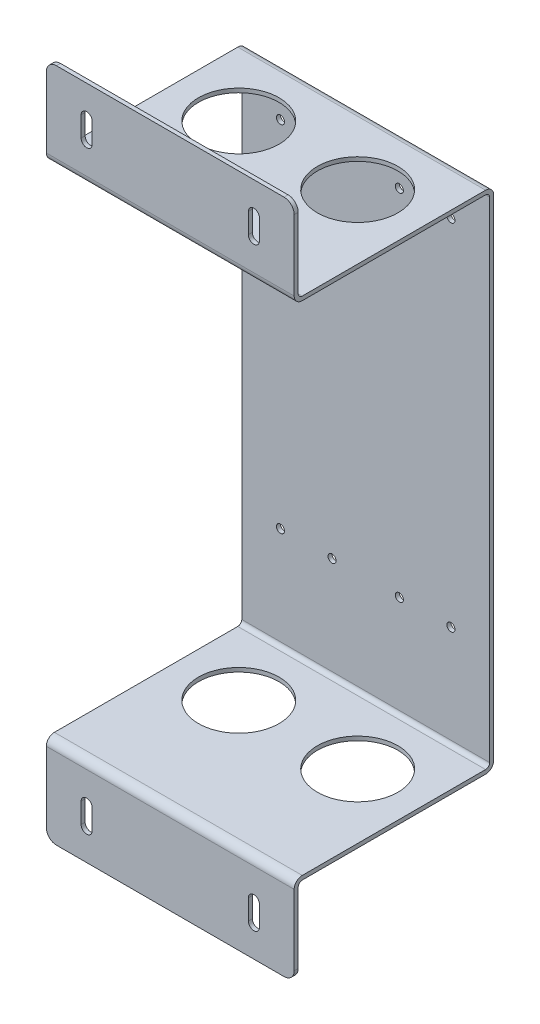
SolidWorks part; units mm, degrees
ref_plane "前视基准面" through (0, 0, 0) normal (0, 0, 1) x (1, 0, 0)
ref_plane "上视基准面" through (0, 0, 0) normal (0, 1, 0) x (1, 0, 0)
ref_plane "右视基准面" through (0, 0, 0) normal (1, 0, 0) x (0, 0, -1)
ref_plane "基准面1" through (0, 0, 49.5) normal (0, 0, 1) x (1, 0, 0)
sketch "草图1" plane through (0, 0, 49.5) normal (0, 0, 1) x (1, 0, 0)
  line L0 (-13.5, -167.5) -> (-13.5, 167.5)
  line L1 (-13.5, 167.5) -> (-136.5, 167.5)
  line L2 (-136.5, 167.5) -> (-136.5, -167.5)
  line L3 (-136.5, -167.5) -> (-13.5, -167.5)
extrude "凸台-拉伸1" add sketch "草图1" against normal blind 99
sketch "草图2" plane through (-13.5, 0, 0) normal (1, 0, 0) x (0, 0, -1)
  line L0 (-49.5, 123.5) -> (-49.5, -123.5)
  line L1 (-49.5, -123.5) -> (47.5, -123.5)
  line L2 (47.5, -123.5) -> (47.5, 123.5)
  line L3 (47.5, 123.5) -> (-49.5, 123.5)
extrude "切除-拉伸1" cut sketch "草图2" against normal through all
sketch "草图3" plane through (-13.5, 0, 0) normal (1, 0, 0) x (0, 0, -1)
  line L0 (49.5, 167.5) -> (-47.5, 167.5)
  line L1 (-47.5, 167.5) -> (-47.5, 125.5)
  line L2 (-47.5, 125.5) -> (49.5, 125.5)
  line L3 (49.5, 125.5) -> (49.5, 167.5)
extrude "切除-拉伸2" cut sketch "草图3" against normal through all
sketch "草图4" plane through (-13.5, 0, 0) normal (1, 0, 0) x (0, 0, -1)
  line L0 (49.5, -167.5) -> (49.5, -125.5)
  line L1 (49.5, -125.5) -> (-47.5, -125.5)
  line L2 (-47.5, -125.5) -> (-47.5, -167.5)
  line L3 (-47.5, -167.5) -> (49.5, -167.5)
extrude "切除-拉伸3" cut sketch "草图4" against normal through all
sketch "草图5" plane through (0, 0, 49.5) normal (0, 0, 1) x (1, 0, 0)
  line L0 (-30.75, 142.5) -> (-30.75, 152.5)
  line L1 (-36.25, 152.5) -> (-36.25, 142.5)
  arc A0 (-36.25, 142.5) -> (-30.75, 142.5) centre (-33.5, 142.5) ccw
  arc A1 (-30.75, 152.5) -> (-36.25, 152.5) centre (-33.5, 152.5) ccw
extrude "切除-拉伸4" cut sketch "草图5" against normal through all
sketch "草图6" plane through (0, 0, 47.5) normal (0, 0, -1) x (-1, 0, 0)
  line L0 (113.75, 152.5) -> (113.75, 142.5)
  line L1 (119.25, 142.5) -> (119.25, 152.5)
  arc A0 (119.25, 152.5) -> (113.75, 152.5) centre (116.5, 152.5) ccw
  arc A1 (113.75, 142.5) -> (119.25, 142.5) centre (116.5, 142.5) ccw
extrude "切除-拉伸5" cut sketch "草图6" against normal through all
sketch "草图7" plane through (0, 0, 49.5) normal (0, 0, 1) x (1, 0, 0)
  line L0 (-30.75, -152.5) -> (-30.75, -142.5)
  line L1 (-36.25, -142.5) -> (-36.25, -152.5)
  arc A0 (-36.25, -152.5) -> (-30.75, -152.5) centre (-33.5, -152.5) ccw
  arc A1 (-30.75, -142.5) -> (-36.25, -142.5) centre (-33.5, -142.5) ccw
extrude "切除-拉伸6" cut sketch "草图7" against normal through all
sketch "草图8" plane through (0, 0, 47.5) normal (0, 0, -1) x (-1, 0, 0)
  line L0 (113.75, -142.5) -> (113.75, -152.5)
  line L1 (119.25, -152.5) -> (119.25, -142.5)
  arc A0 (119.25, -142.5) -> (113.75, -142.5) centre (116.5, -142.5) ccw
  arc A1 (113.75, -152.5) -> (119.25, -152.5) centre (116.5, -152.5) ccw
extrude "切除-拉伸7" cut sketch "草图8" against normal through all
hole_wizard "M4 螺纹孔1" positions "草图10" profile "草图9" tap size "M4" standard "ISO" end condition through all
sketch "草图10" plane through (0, 0, -47.5) normal (0, 0, 1) x (1, 0, 0)
  point P0 (-117.3, -72.9)
sketch "草图9" plane through (-117.3, -72.9, -47.5) normal (1, 0, 0) x (0, -1, 0)
  line L0 (0, 0) -> (0, 2)
  line L1 (0, 2) -> (2, 2)
  line L2 (2, 2) -> (2, 0)
  line L5 (2, 0) -> (0, 0)
  line L11 (0, -6.35) -> (0, 107.95) construction
  dimension "螺纹线主直径" = 4
  dimension "通孔螺纹孔钻头深度" = 2
hole_wizard "M4 螺纹孔2" positions "草图12" profile "草图11" tap size "M4" standard "ISO" end condition through all
sketch "草图12" plane through (0, 0, -47.5) normal (0, 0, 1) x (1, 0, 0)
  point P0 (-91.7, -72.9)
sketch "草图11" plane through (-91.7, -72.9, -47.5) normal (1, 0, 0) x (0, -1, 0)
  line L0 (0, 0) -> (0, 2)
  line L1 (0, 2) -> (2, 2)
  line L2 (2, 2) -> (2, 0)
  line L5 (2, 0) -> (0, 0)
  line L11 (0, -6.35) -> (0, 107.95) construction
  dimension "螺纹线主直径" = 4
  dimension "通孔螺纹孔钻头深度" = 2
hole_wizard "M4 螺纹孔3" positions "草图14" profile "草图13" tap size "M4" standard "ISO" end condition through all
sketch "草图14" plane through (0, 0, -47.5) normal (0, 0, 1) x (1, 0, 0)
  point P0 (-32.7, -72.9)
sketch "草图13" plane through (-32.7, -72.9, -47.5) normal (1, 0, 0) x (0, -1, 0)
  line L0 (0, 0) -> (0, 2)
  line L1 (0, 2) -> (2, 2)
  line L2 (2, 2) -> (2, 0)
  line L5 (2, 0) -> (0, 0)
  line L11 (0, -6.35) -> (0, 107.95) construction
  dimension "螺纹线主直径" = 4
  dimension "通孔螺纹孔钻头深度" = 2
hole_wizard "M4 螺纹孔4" positions "草图16" profile "草图15" tap size "M4" standard "ISO" end condition through all
sketch "草图16" plane through (0, 0, -47.5) normal (0, 0, 1) x (1, 0, 0)
  point P0 (-58.3, -72.9)
sketch "草图15" plane through (-58.3, -72.9, -47.5) normal (1, 0, 0) x (0, -1, 0)
  line L0 (0, 0) -> (0, 2)
  line L1 (0, 2) -> (2, 2)
  line L2 (2, 2) -> (2, 0)
  line L5 (2, 0) -> (0, 0)
  line L11 (0, -6.35) -> (0, 107.95) construction
  dimension "螺纹线主直径" = 4
  dimension "通孔螺纹孔钻头深度" = 2
hole_wizard "M4 螺纹孔5" positions "草图18" profile "草图17" tap size "M4" standard "ISO" end condition through all
sketch "草图18" plane through (0, 0, -47.5) normal (0, 0, 1) x (1, 0, 0)
  point P0 (-91.7, 102.9)
sketch "草图17" plane through (-91.7, 102.9, -47.5) normal (1, 0, 0) x (0, -1, 0)
  line L0 (0, 0) -> (0, 2)
  line L1 (0, 2) -> (2, 2)
  line L2 (2, 2) -> (2, 0)
  line L5 (2, 0) -> (0, 0)
  line L11 (0, -6.35) -> (0, 107.95) construction
  dimension "螺纹线主直径" = 4
  dimension "通孔螺纹孔钻头深度" = 2
hole_wizard "M4 螺纹孔6" positions "草图20" profile "草图19" tap size "M4" standard "ISO" end condition through all
sketch "草图20" plane through (0, 0, -47.5) normal (0, 0, 1) x (1, 0, 0)
  point P0 (-117.3, 102.9)
sketch "草图19" plane through (-117.3, 102.9, -47.5) normal (1, 0, 0) x (0, -1, 0)
  line L0 (0, 0) -> (0, 2)
  line L1 (0, 2) -> (2, 2)
  line L2 (2, 2) -> (2, 0)
  line L5 (2, 0) -> (0, 0)
  line L11 (0, -6.35) -> (0, 107.95) construction
  dimension "螺纹线主直径" = 4
  dimension "通孔螺纹孔钻头深度" = 2
hole_wizard "M4 螺纹孔7" positions "草图22" profile "草图21" tap size "M4" standard "ISO" end condition through all
sketch "草图22" plane through (0, 0, -47.5) normal (0, 0, 1) x (1, 0, 0)
  point P0 (-32.7, 102.9)
sketch "草图21" plane through (-32.7, 102.9, -47.5) normal (1, 0, 0) x (0, -1, 0)
  line L0 (0, 0) -> (0, 2)
  line L1 (0, 2) -> (2, 2)
  line L2 (2, 2) -> (2, 0)
  line L5 (2, 0) -> (0, 0)
  line L11 (0, -6.35) -> (0, 107.95) construction
  dimension "螺纹线主直径" = 4
  dimension "通孔螺纹孔钻头深度" = 2
hole_wizard "M4 螺纹孔8" positions "草图24" profile "草图23" tap size "M4" standard "ISO" end condition through all
sketch "草图24" plane through (0, 0, -47.5) normal (0, 0, 1) x (1, 0, 0)
  point P0 (-58.3, 102.9)
sketch "草图23" plane through (-58.3, 102.9, -47.5) normal (1, 0, 0) x (0, -1, 0)
  line L0 (0, 0) -> (0, 2)
  line L1 (0, 2) -> (2, 2)
  line L2 (2, 2) -> (2, 0)
  line L5 (2, 0) -> (0, 0)
  line L11 (0, -6.35) -> (0, 107.95) construction
  dimension "螺纹线主直径" = 4
  dimension "通孔螺纹孔钻头深度" = 2
hole_wizard "孔9" positions "草图26" profile "草图25" legacy
sketch "草图26" plane through (0, -125.5, 0) normal (0, -1, 0) x (1, 0, 0)
  point P0 (-45.5, -14)
sketch "草图25" plane through (-45.5, -125.5, -14) normal (1, 0, 0) x (0, 0, -1)
  line L0 (0, 0) -> (0, 2)
  line L1 (0, 2) -> (20, 2)
  line L2 (20, 2) -> (20, 0)
  line L3 (20, 0) -> (0, 0)
  line L4 (0, 110) -> (0, -10) construction
  dimension "直径" = 40
  dimension "深度" = 2
hole_wizard "孔10" positions "草图28" profile "草图27" legacy
sketch "草图28" plane through (0, -125.5, 0) normal (0, -1, 0) x (1, 0, 0)
  point P0 (-104.5, -14)
sketch "草图27" plane through (-104.5, -125.5, -14) normal (1, 0, 0) x (0, 0, -1)
  line L0 (0, 0) -> (0, 2)
  line L1 (0, 2) -> (20, 2)
  line L2 (20, 2) -> (20, 0)
  line L3 (20, 0) -> (0, 0)
  line L4 (0, 110) -> (0, -10) construction
  dimension "直径" = 40
  dimension "深度" = 2
hole_wizard "孔11" positions "草图30" profile "草图29" legacy
sketch "草图30" plane through (0, 125.5, 0) normal (0, 1, 0) x (-1, 0, 0)
  point P0 (104.5, -14)
sketch "草图29" plane through (-104.5, 125.5, -14) normal (1, 0, 0) x (0, 0, 1)
  line L0 (0, 0) -> (0, 293)
  line L1 (0, 293) -> (20, 293)
  line L2 (20, 293) -> (20, 0)
  line L3 (20, 0) -> (0, 0)
  line L4 (0, 110) -> (0, -10) construction
  dimension "直径" = 40
  dimension "深度" = 293
hole_wizard "孔12" positions "草图32" profile "草图31" legacy
sketch "草图32" plane through (0, 125.5, 0) normal (0, 1, 0) x (-1, 0, 0)
  point P0 (45.5, -14)
sketch "草图31" plane through (-45.5, 125.5, -14) normal (1, 0, 0) x (0, 0, 1)
  line L0 (0, 0) -> (0, 293)
  line L1 (0, 293) -> (20, 293)
  line L2 (20, 293) -> (20, 0)
  line L3 (20, 0) -> (0, 0)
  line L4 (0, 110) -> (0, -10) construction
  dimension "直径" = 40
  dimension "深度" = 293
fillet "圆角1" radius 2 1 edges at (-75, 125.5, 47.5)
fillet "圆角2" radius 2 1 edges at (-75, -125.5, 47.5)
fillet "圆角3" radius 2 1 edges at (-75, -123.5, -47.5)
fillet "圆角4" radius 2 1 edges at (-75, 123.5, -47.5)
fillet "圆角5" radius 4 1 edges at (-75, 123.5, 49.5)
fillet "圆角6" radius 4 1 edges at (-75, -123.5, 49.5)
fillet "圆角7" radius 4 1 edges at (-75, -125.5, -49.5)
fillet "圆角8" radius 4 1 edges at (-75, 125.5, -49.5)
fillet "圆角9" radius 5 1 edges at (-136.5, -167.5, 48.5)
fillet "圆角10" radius 5 1 edges at (-136.5, 167.5, 48.5)
fillet "圆角11" radius 5 1 edges at (-13.5, -167.5, 48.5)
fillet "圆角12" radius 5 1 edges at (-13.5, 167.5, 48.5)
